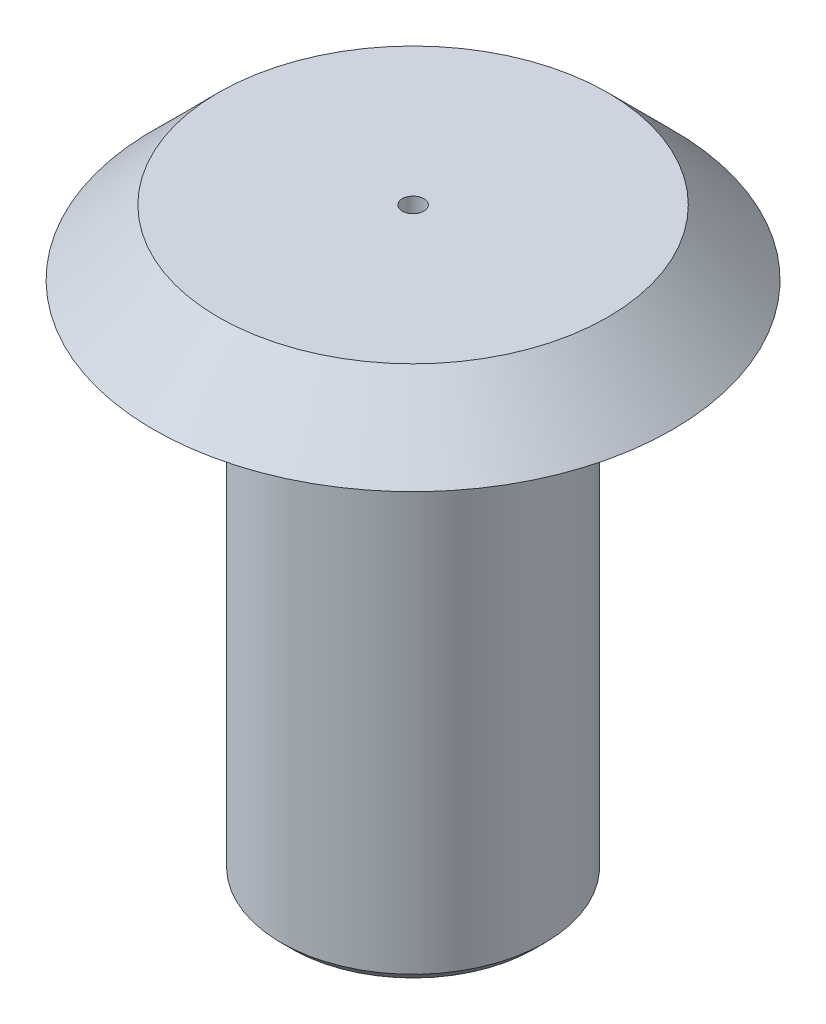
SolidWorks part; units mm, degrees
material "ABS"
ref_plane "Front Plane" through (0, 0, 0) normal (0, 0, 1) x (1, 0, 0)
ref_plane "Top Plane" through (0, 0, 0) normal (0, 1, 0) x (1, 0, 0)
ref_plane "Right Plane" through (0, 0, 0) normal (1, 0, 0) x (0, 0, -1)
sketch "Sketch2" plane through (0, 0, 0) normal (0, 0, 1) x (1, 0, 0)
  line L0 (0, -747.5123) -> (0, 36628.1018) construction
  line L3 (12, 0) -> (9, 3)
  line L6 (1, 3) -> (9, 3)
  line L7 (12, 0) -> (9, 0)
  line L8 (9, 0) -> (8, 1)
  line L9 (8, 1) -> (6.1, 1)
  line L10 (6.1, 1) -> (6.1, -24)
  line L11 (6.1, -24) -> (1, -24)
  line L12 (1, -24) -> (1, -23.118)
  line L13 (1, -22.5) -> (1, -21.5) construction
  line L14 (1, -20.882) -> (1, 1.1893)
  line L17 (1, 1.5) -> (1, 3) construction
  line L18 (0.5, 2.3107) -> (0.5, 3)
  line L19 (0.5, 3) -> (1, 3)
  line L20 (0.7803, 1.7197) -> (0.7197, 1.7803)
  arc A0 (0.6667, -21.6273) -> (0.6667, -22.3727) centre (1, -22) ccw
  arc A1 (0.6667, -22.3727) -> (1, -23.118) centre (0, -23.118) cw
  arc A2 (0.6667, -21.6273) -> (1, -20.882) centre (0, -20.882) ccw
  arc A3 (0.7803, 1.7197) -> (1, 1.1893) centre (0.25, 1.1893) cw
  arc A4 (0.7197, 1.7803) -> (0.5, 2.3107) centre (1.25, 2.3107) cw
  point P4 (8.8458, 3)
  point P5 (0.5, 6.5923)
  point P30 (0.5, 2)
  point P31 (4, 9.038)
  point P32 (12.3214, 0)
  point P33 (12.304, 0.0174)
  dimension "D11" = 1
  dimension "D12" = 1
  dimension "D16" = 0.75
  dimension "D1" = 3
  dimension "D2" = 2
  dimension "D3" = 24
  dimension "D6" = 24
  dimension "D7" = 2
  dimension "D8" = 12.2
  dimension "D9" = 45
  dimension "D10" = 1
  dimension "D13" = 2
  dimension "D14" = 1
  dimension "D15" = 1
revolve "Revolve1" add sketch "Sketch2" angle 360 about L0
chamfer "Chamfer2" distance 0.5 angle 45 3 edges at (1, -24, 0) (6.1, 1, 0) (6.1, -24, 0)
